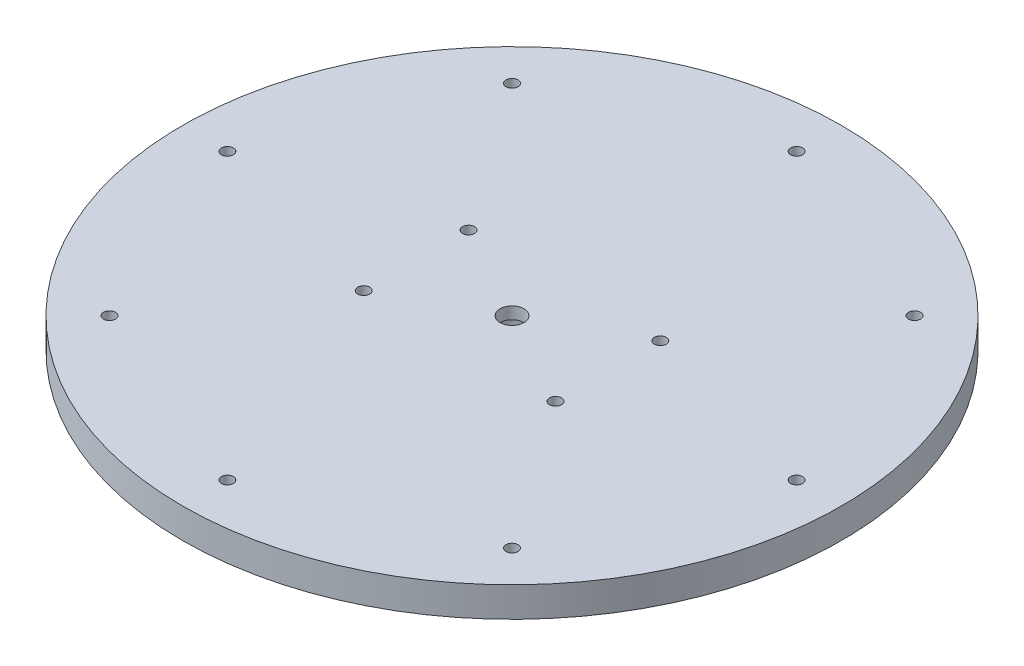
SolidWorks part; units mm, degrees
ref_plane "Front Plane" through (0, 0, 0) normal (0, 0, 1) x (1, 0, 0)
ref_plane "Top Plane" through (0, 0, 0) normal (0, 1, 0) x (1, 0, 0)
ref_plane "Right Plane" through (0, 0, 0) normal (1, 0, 0) x (0, 0, -1)
sketch "Sketch2" plane through (0, 0, 0) normal (0, 1, 0) x (1, 0, 0)
  circle A1 centre (0, 0) radius 110
extrude "Boss-Extrude2" add sketch "Sketch2" along normal blind 10
sketch "Sketch4" plane through (0, 0, 0) normal (0, -1, 0) x (-1, 0, 0)
  line L0 (0, 0) -> (62.6686, -64.5961) construction
  line L1 (62.6686, -64.5961) -> (-62.6686, 64.5961) construction
  circle A0 centre (0, 0) radius 9.5
  circle A1 centre (0, 0) radius 3
extrude "Cut-Extrude1" cut sketch "Sketch4" against normal blind 6 contours A0
sketch "Sketch6" plane through (0, 6, 0) normal (0, -1, 0) x (-1, 0, 0)
  line L0 (0, 0) -> (62.6686, -64.5961) construction
  line L1 (62.6686, -64.5961) -> (-62.6686, 64.5961) construction
  circle A0 centre (0, 0) radius 4
  dimension "D1" = 8
extrude "Cut-Extrude3" cut sketch "Sketch6" against normal through all contours A0
sketch "Sketch7" plane through (0, 0, 0) normal (0, -1, 0) x (-1, 0, 0)
  line L1 (32, -17.5) -> (-32, -17.5)
  line L2 (32, -17.5) -> (32, 17.5)
  line L3 (32, 17.5) -> (-32, 17.5)
  line L4 (-32, -17.5) -> (-32, 17.5)
  line L5 (32, -17.5) -> (-32, 17.5) construction
  line L6 (32, 17.5) -> (-32, -17.5) construction
  circle A0 centre (32, -17.5) radius 2
  circle A1 centre (32, 17.5) radius 2
  circle A2 centre (-32, 17.5) radius 2
  circle A3 centre (-32, -17.5) radius 2
  point P0 (0, 0)
  dimension "D3" = 4
  dimension "D4" = 4
  dimension "D5" = 4
  dimension "D6" = 4
  dimension "D1" = 35
  dimension "D2" = 64
extrude "Cut-Extrude6" cut sketch "Sketch7" against normal through all contours A0 | A1 | A3 | A2
sketch "Sketch8" plane through (0, 0, 0) normal (0, -1, 0) x (1, 0, 0)
  line L0 (0, 0) -> (0, 131.1144) construction
  circle A0 centre (0, 95) radius 2
  circle A1 centre (67.1751, 67.1751) radius 2
  circle A2 centre (95, 0) radius 2
  circle A3 centre (67.1751, -67.1751) radius 2
  circle A4 centre (0, -95) radius 2
  circle A5 centre (-67.1751, -67.1751) radius 2
  circle A6 centre (-95, 0) radius 2
  circle A7 centre (-67.1751, 67.1751) radius 2
  point P21 (0, 0)
  dimension "D1" = 4
  dimension "D2" = 95
  dimension "D3" = 8
extrude "Cut-Extrude7" cut sketch "Sketch8" against normal blind 10
